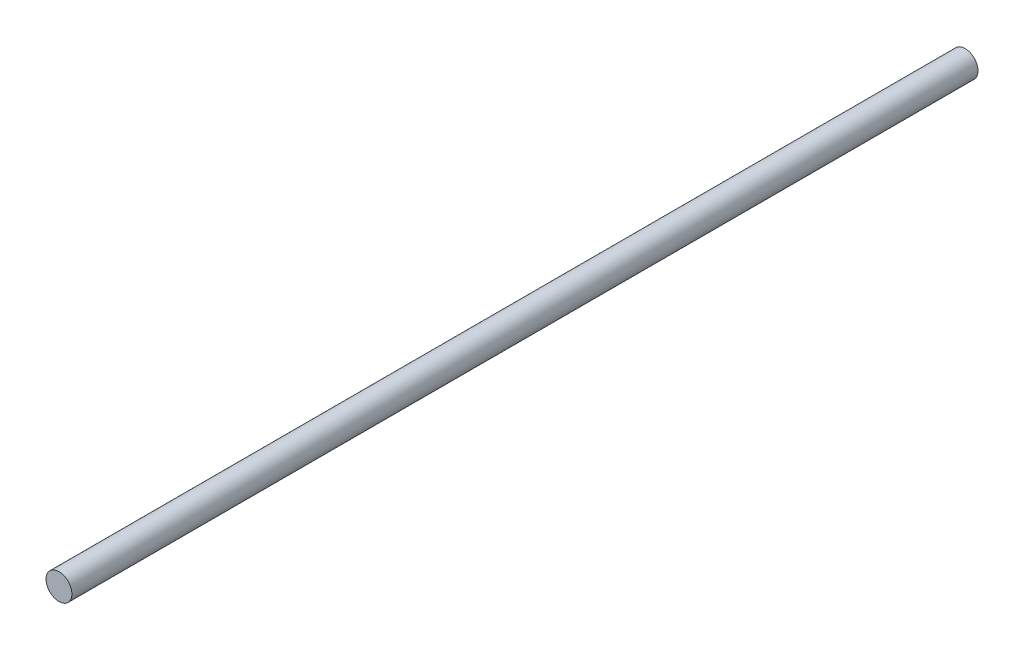
SolidWorks part; units mm, degrees
material "1023 Carbon Steel Sheet (SS)"
ref_plane "Front" through (0, 0, 0) normal (0, 0, 1) x (1, 0, 0)
ref_plane "Top" through (0, 0, 0) normal (0, 1, 0) x (1, 0, 0)
ref_plane "Right" through (0, 0, 0) normal (1, 0, 0) x (0, 0, -1)
ref_plane "Plane1" through (0, 0, 0) normal (0, -1, 0) x (1, 0, 0)
sketch "Sketch1" plane through (0, 0, 0) normal (0, -1, 0) x (1, 0, 0)
  line L0 (1.5, 105) -> (0, 105)
  line L1 (0, 105) -> (0, 0)
  line L2 (0, 0) -> (1.5, 0)
  line L3 (1.5, 0) -> (1.5, 105)
  line L4 (0, 105) -> (0, 0) construction
revolve "Revolve1" add sketch "Sketch1" angle 360 about L4
